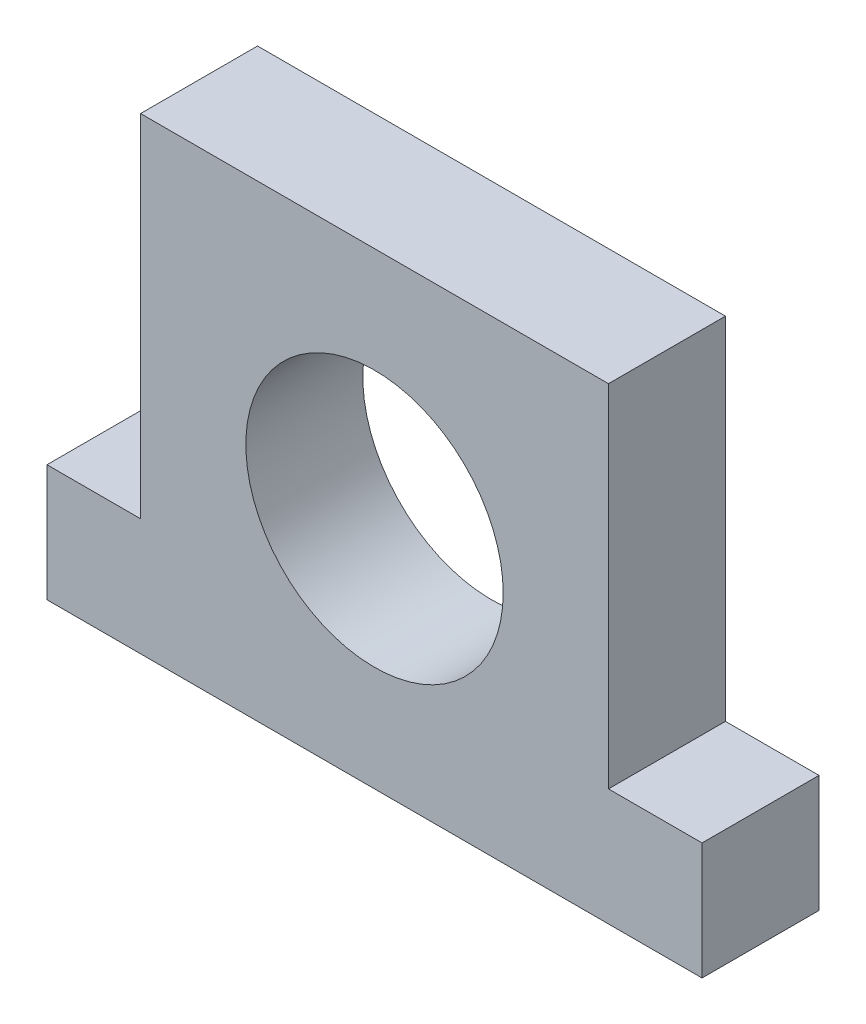
SolidWorks part; units mm, degrees
ref_plane "Front Plane" through (0, 0, 0) normal (0, 0, 1) x (1, 0, 0)
ref_plane "Top Plane" through (0, 0, 0) normal (0, 1, 0) x (1, 0, 0)
ref_plane "Right Plane" through (0, 0, 0) normal (1, 0, 0) x (0, 0, -1)
sketch "Sketch1" plane through (0, 0, 0) normal (0, 0, 1) x (1, 0, 0)
  line L0 (28, 0) -> (-28, 0)
  line L1 (-28, 0) -> (-28, 10)
  line L2 (-28, 10) -> (-20, 10)
  line L3 (-20, 10) -> (-20, 40)
  line L4 (-20, 40) -> (20, 40)
  line L5 (0, 40) -> (0, 0) construction
  line L6 (28, 10) -> (20, 10)
  line L7 (28, 0) -> (28, 10)
  line L8 (20, 10) -> (20, 40)
  circle A0 centre (0, 20) radius 11
  point P13 (0, 0)
  dimension "D5" = 22
  dimension "D1" = 20
  dimension "D2" = 28
  dimension "D3" = 10
  dimension "D4" = 40
  dimension "D6" = 20
extrude "Boss-Extrude1" add sketch "Sketch1" along normal blind 10
